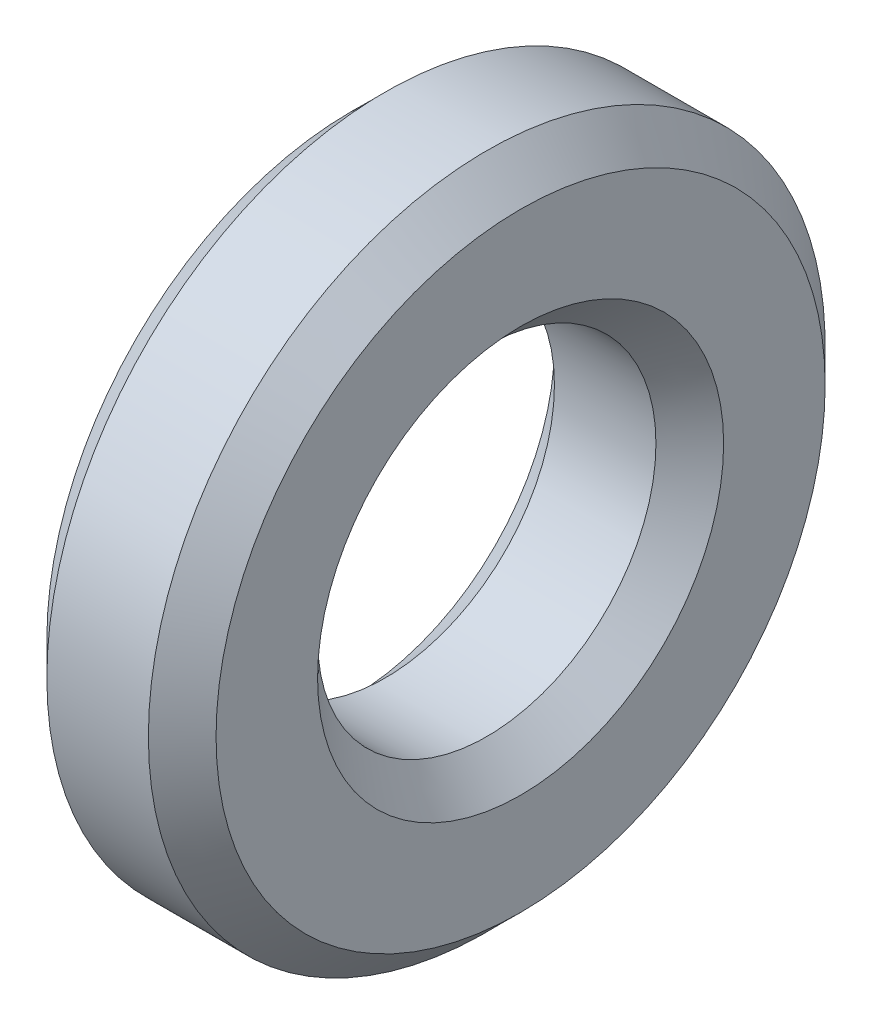
SolidWorks part; units mm, degrees
material "S45C相当"
ref_plane "Front Plane" through (0, 0, 0) normal (0, 0, 1) x (1, 0, 0)
ref_plane "Top Plane" through (0, 0, 0) normal (0, 1, 0) x (1, 0, 0)
ref_plane "Right Plane" through (0, 0, 0) normal (1, 0, 0) x (0, 0, -1)
sketch "Sketch1" plane through (0, 0, 0) normal (0, 0, 1) x (1, 0, 0)
  line L0 (0, 0) -> (1, 0) construction
  line L2 (0, 1) -> (1, 1)
  line L3 (0, 1) -> (0, 2)
  line L4 (0, 2) -> (1, 2)
  line L5 (1, 1) -> (1, 2)
  dimension "D" = 4
  dimension "V" = 2
  dimension "T" = 1
revolve "Revolve1" add sketch "Sketch1" angle 360 about L0
chamfer "Chamfer1" distance 0.2 angle 45 4 edges at (0, 0, 2) (1, 0, 2) (1, 0, 1) (0, 0, 1)
